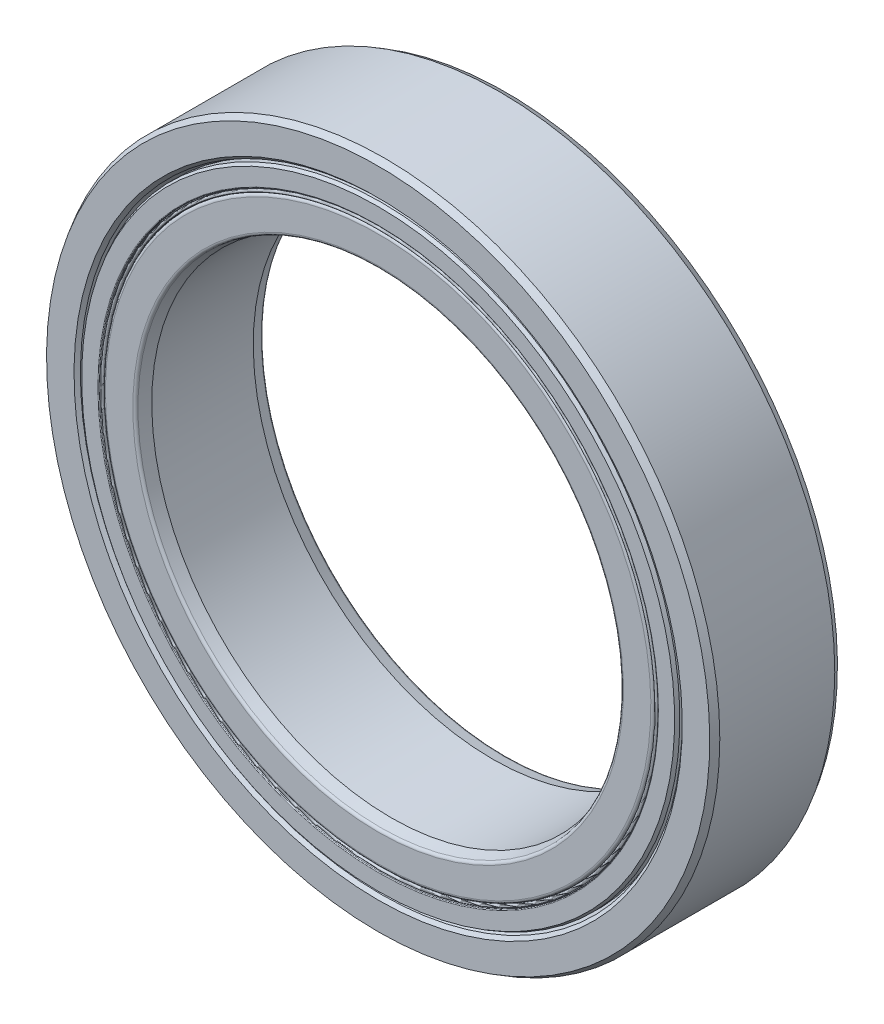
SolidWorks part; units mm, degrees
ref_plane "Front Plane" through (0, 0, 0) normal (0, 0, 1) x (1, 0, 0)
ref_plane "Top Plane" through (0, 0, 0) normal (0, 1, 0) x (1, 0, 0)
ref_plane "Right Plane" through (0, 0, 0) normal (1, 0, 0) x (0, 0, -1)
sketch "Sketch1" plane through (0, 0, 0) normal (0, 0, 1) x (1, 0, 0)
  line L0 (-10.5, 0) -> (10.5, 0) construction
  line L1 (-7.5, 0) -> (7.5, 0) construction
  circle A0 centre (0, 0) radius 7.5 construction
  circle A1 centre (0, 0) radius 10.5 construction
  point P3 (0, 0)
  point P6 (0, 0)
  point P7 (0, -7.5)
  point P11 (0, -10.5)
  point P12 (0, 7.5)
  point P13 (0, 10.5)
  dimension "OD" = 21
  dimension "ID" = 15
sketch "Sketch2" plane through (0, 0, 0) normal (1, 0, 0) x (0, 0, -1)
  line L0 (-2, 10.5) -> (2, 10.5) construction
  line L1 (0, 10.5) -> (0, -10.5) construction
  line L2 (1.8, 10.5) -> (-1.8, 10.5)
  line L3 (-1.8, 10.5) -> (-2, 10.3845)
  line L4 (-2, 10.3845) -> (-2, 9.524)
  line L5 (-1.683, 9.345) -> (-1.0675, 9.345)
  line L6 (1.683, 9.345) -> (1.0675, 9.345)
  line L7 (2, 10.3845) -> (2, 9.524)
  line L8 (1.8, 10.5) -> (2, 10.3845)
  line L9 (-1.0675, 9.345) -> (-1.0675, 9.73) construction
  line L10 (-1.0675, 9.73) -> (-1.0675, 10.115) construction
  line L11 (0, 10.5) -> (0, -10.5) construction
  line L12 (-2, 0) -> (2, 0) construction
  line L13 (2, 7.5) -> (-2, 7.5) construction
  line L14 (-2, 7.5) -> (-2, -7.5) construction
  line L15 (-2, -7.5) -> (2, -7.5) construction
  line L16 (2, 10.5) -> (2, -10.5) construction
  line L17 (-1.0675, 10.115) -> (-1.0675, 10.5) construction
  line L18 (-1.0675, 10.115) -> (0, 10.115) construction
  line L20 (-1.683, 9.345) -> (-1.9, 9.424)
  line L21 (-1.9, 9.424) -> (-2, 9.524)
  line L26 (1.9, 9.424) -> (2, 9.524)
  line L27 (1.683, 9.345) -> (1.9, 9.424)
  arc A0 (-1.0675, 9.345) -> (1.0675, 9.345) centre (0, 8.99) cw
  circle A1 centre (0, 8.99) radius 1.125 construction
  point P17 (0, 0)
  point P21 (0, 10.5)
  point P30 (0, -7.5)
  dimension "Approx. Ball Dia." = 2.25
  dimension "Width" = 4
  dimension "For Shaft Diameter" = 15
  dimension "For Housing ID" = 21
  dimension "D4" = 18.69
  dimension "D2" = 20
  dimension "D5" = 45
  dimension "D1" = 30
  dimension "D6" = 0.2
  dimension "D7" = 0.1
sketch "Sketch3" plane through (0, 0, 0) normal (1, 0, 0) x (0, 0, -1)
  line L14 (-1.683, 9.345) -> (-1.9, 9.424) construction
  line L15 (-1.9, 9.424) -> (-2, 9.524) construction
  line L16 (-2, 10.3845) -> (-2, 9.524) construction
  line L17 (-1.8, 10.5) -> (-2, 10.3845) construction
  line L18 (1.8, 10.5) -> (-1.8, 10.5) construction
  line L19 (1.8, 10.5) -> (2, 10.3845) construction
  line L20 (2, 10.3845) -> (2, 9.524) construction
  line L21 (1.9, 9.424) -> (2, 9.524) construction
  line L22 (1.683, 9.345) -> (1.9, 9.424) construction
  line L23 (1.683, 9.345) -> (1.0675, 9.345) construction
  line L24 (-1.683, 9.345) -> (-1.0675, 9.345) construction
  line L25 (-1.683, 9.345) -> (-1.9, 9.424)
  line L26 (-1.9, 9.424) -> (-2, 9.524)
  line L27 (-2, 10.3845) -> (-2, 9.524)
  line L28 (-1.8, 10.5) -> (-2, 10.3845)
  line L29 (1.8, 10.5) -> (-1.8, 10.5)
  line L30 (1.8, 10.5) -> (2, 10.3845)
  line L31 (2, 10.3845) -> (2, 9.524)
  line L32 (1.9, 9.424) -> (2, 9.524)
  line L33 (1.683, 9.345) -> (1.9, 9.424)
  line L34 (1.683, 9.345) -> (1.0675, 9.345)
  line L35 (-1.683, 9.345) -> (-1.0675, 9.345)
  arc A2 (1.0675, 9.345) -> (-1.0675, 9.345) centre (0, 8.99) ccw construction
  arc A3 (1.0675, 9.345) -> (-1.0675, 9.345) centre (0, 8.99) ccw
revolve "Revolve1" add sketch "Sketch3" angle 360 about L12
sketch "Sketch4" plane through (0, 0, 0) normal (1, 0, 0) x (0, 0, -1)
  line L0 (0, 10.5) -> (0, -10.5) construction
  line L1 (0, 10.5) -> (0, -10.5) construction
  line L2 (-1.5894, 7.5) -> (-1.93, 7.5912)
  line L3 (-2, 7.6825) -> (-2, 8.5405)
  line L4 (2, -10.3845) -> (2, 10.3845) construction
  line L5 (-1.9055, 8.635) -> (-1.0675, 8.635)
  line L6 (-1.5894, 7.5) -> (1.5894, 7.5)
  line L7 (2, 10.3845) -> (2, 9.524) construction
  line L8 (1.5894, 7.5) -> (1.93, 7.5912)
  line L9 (0, 10.115) -> (0, 7.5) construction
  line L10 (2, 7.6825) -> (2, 8.5405)
  line L11 (1.9055, 8.635) -> (1.0675, 8.635)
  line L12 (1.5894, 7.5) -> (1.5894, 7.5912) construction
  line L13 (1.5894, 7.5912) -> (1.5894, 7.6825) construction
  line L14 (1.5894, 7.6825) -> (1.5894, 7.7738) construction
  line L15 (1.5894, 7.7738) -> (1.5894, 7.865) construction
  circle A0 centre (0, 8.99) radius 1.125 construction
  arc A1 (1.0675, 8.635) -> (-1.0675, 8.635) centre (0, 8.99) cw
  arc A2 (2, 8.5405) -> (1.9055, 8.635) centre (1.9055, 8.5405) ccw
  arc A3 (-2, 8.5405) -> (-1.9055, 8.635) centre (-1.9055, 8.5405) cw
  arc A4 (1.93, 7.5912) -> (2, 7.6825) centre (1.9055, 7.6825) ccw
  arc A5 (-1.93, 7.5912) -> (-2, 7.6825) centre (-1.9055, 7.6825) cw
  point P14 (2, 7.61)
  point P36 (0, 7.865)
  dimension "D1" = 15
revolve "Revolve2" add sketch "Sketch4" angle 360 about L12
sketch "Sketch5" plane through (0, 0, 0) normal (1, 0, 0) x (0, 0, -1)
  line L0 (-1.125, 8.99) -> (1.125, 8.99)
  arc A2 (-1.125, 8.99) -> (1.125, 8.99) centre (0, 8.99) cw
  arc A3 (1.0675, 9.345) -> (-1.0675, 9.345) centre (0, 8.99) ccw construction
revolve "Revolve3" add sketch "Sketch5" angle 360 about L0
pattern_circular "CirPattern1" count 16 over 360 about axis through (0, 0, 0) along (0, 0, 1) of bodies 104
sketch "Sketch6" plane through (0, 0, 0) normal (1, 0, 0) x (0, 0, -1)
  line L1 (-1.8961, 9.345) -> (-1.125, 9.345)
  line L2 (-2, 9.285) -> (-2, 8.779)
  line L3 (-1.976, 8.755) -> (-1.125, 8.755)
  line L4 (-1.125, 9.345) -> (-1.125, 8.755)
  line L5 (-2, 7.6825) -> (-2, 8.5405) construction
  line L6 (-1.8, 10.5) -> (-2, 10.3845) construction
  line L7 (0, 10.5) -> (0, 7.5) construction
  line L8 (1.976, 8.755) -> (1.125, 8.755)
  line L9 (1.125, 9.345) -> (1.125, 8.755)
  line L10 (1.8961, 9.345) -> (1.125, 9.345)
  line L11 (2, 9.285) -> (2, 8.779)
  line L13 (-1.9055, 8.635) -> (-1.0675, 8.635) construction
  line L14 (-2, 9.285) -> (-1.8961, 9.345)
  line L15 (-1.683, 9.345) -> (-1.0675, 9.345) construction
  line L16 (2, 9.285) -> (1.8961, 9.345)
  arc A0 (-2, 8.779) -> (-1.976, 8.755) centre (-1.976, 8.779) ccw
  circle A1 centre (0, 8.99) radius 1.125 construction
  arc A2 (2, 8.779) -> (1.976, 8.755) centre (1.976, 8.779) cw
  point P26 (-2, 8.755)
  dimension "D3" = 0.024
  dimension "D1" = 0.12
  dimension "D2" = 0.06
revolve "Revolve4" add sketch "Sketch6" angle 360 about L12
sketch "Sketch7" plane through (0, 0, 0) normal (1, 0, 0) x (0, 0, -1)
  line L3 (-1.125, 8.755) -> (-1.9026, 8.755)
  line L4 (-1.976, 8.755) -> (-1.125, 8.755) construction
  line L7 (0, 7.865) -> (0, 7.5) construction
  line L8 (0, 10.5) -> (0, -10.5) construction
  line L21 (-1.9026, 8.755) -> (-1.9322, 8.7498)
  line L22 (-1.93, 8.725) -> (-1.955, 8.725)
  line L23 (-1.955, 8.635) -> (-1.125, 8.635)
  line L24 (-1.125, 8.635) -> (-1.125, 8.755)
  line L25 (-1.9055, 8.635) -> (-1.0675, 8.635) construction
  line L26 (-2, 8.779) -> (-2, 8.635) construction
  line L27 (-2, 8.635) -> (-1.955, 8.635) construction
  line L28 (-1.9026, 8.755) -> (-1.9026, 8.725) construction
  line L29 (-1.9026, 8.725) -> (-1.9026, 8.695) construction
  line L30 (-1.9026, 8.695) -> (-1.9026, 8.665) construction
  line L31 (-1.9026, 8.665) -> (-1.9026, 8.635) construction
  circle A2 centre (0, 8.99) radius 1.125 construction
  arc A9 (-1.9322, 8.7498) -> (-1.93, 8.725) centre (-1.93, 8.7375) ccw
  arc A10 (-1.955, 8.725) -> (-1.955, 8.635) centre (-1.955, 8.68) ccw
  dimension "D1" = 0.025
  dimension "D2" = 10
revolve "Revolve5" add sketch "Sketch7" angle 360 about L12
equation "\"D4@Sketch2\"=\"OD@Sketch1\"*.89"
equation "\"D1@Sketch6\"=(\"OD@Sketch1\"-\"ID@Sketch1\")*.02"
equation "\"D2@Sketch6\"=\"D1@Sketch6\"*.5"
equation "\"D3@Sketch6\"=\"D1@Sketch6\"*.2"
equation "\"D6@Sketch2\"=\"Width@Sketch2\"*.05"
equation "\"D7@Sketch2\"=\"D6@Sketch2\"*.5"
equation "\"D1@CirPattern1\" =  ( pi * \"OD@Sketch1\" )  * .5625 / \"Approx. Ball Dia.@Sketch2\""
equation "\"Approx. Ball Dia.@Sketch2\"=(\"OD@Sketch1\"-\"ID@Sketch1\")*.5*.75"
